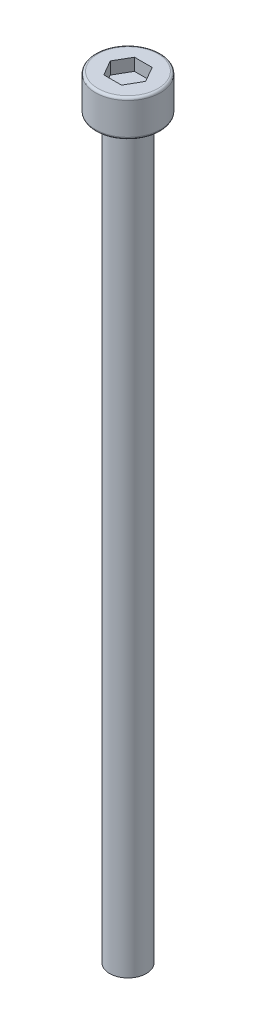
SolidWorks part; units mm, degrees
ref_plane "Front Plane" through (0, 0, 0) normal (0, 0, 1) x (1, 0, 0)
ref_plane "Top Plane" through (0, 0, 0) normal (0, 1, 0) x (1, 0, 0)
ref_plane "Right Plane" through (0, 0, 0) normal (1, 0, 0) x (0, 0, -1)
sketch "Sketch1" plane through (0, 0, 0) normal (0, 1, 0) x (1, 0, 0)
  circle A0 centre (0, 0) radius 2.65
  dimension "D1" = 5.3
extrude "Boss-Extrude1" add sketch "Sketch1" along normal blind 3
sketch "Sketch2" plane through (0, 3, 0) normal (0, 1, 0) x (1, 0, 0)
  line L1 (1.4434, 0) -> (0.7217, 1.25)
  line L2 (0.7217, 1.25) -> (-0.7217, 1.25)
  line L3 (-0.7217, 1.25) -> (-1.4434, 0)
  line L4 (-1.4434, 0) -> (-0.7217, -1.25)
  line L5 (-0.7217, -1.25) -> (0.7217, -1.25)
  line L6 (0.7217, -1.25) -> (1.4434, 0)
  circle A0 centre (0, 0) radius 1.25 construction
  dimension "D1" = 2.5
extrude "Cut-Extrude1" cut sketch "Sketch2" against normal blind 1
sketch "Sketch3" plane through (0, 0, 0) normal (0, -1, 0) x (1, 0, 0)
  circle A0 centre (0, 0) radius 1.5
  dimension "D1" = 3
extrude "Boss-Extrude2" add sketch "Sketch3" along normal blind 60
fillet "Fillet1" radius 0.2 2 edges at (0, 0, 2.65) (0, 3, 2.65)
